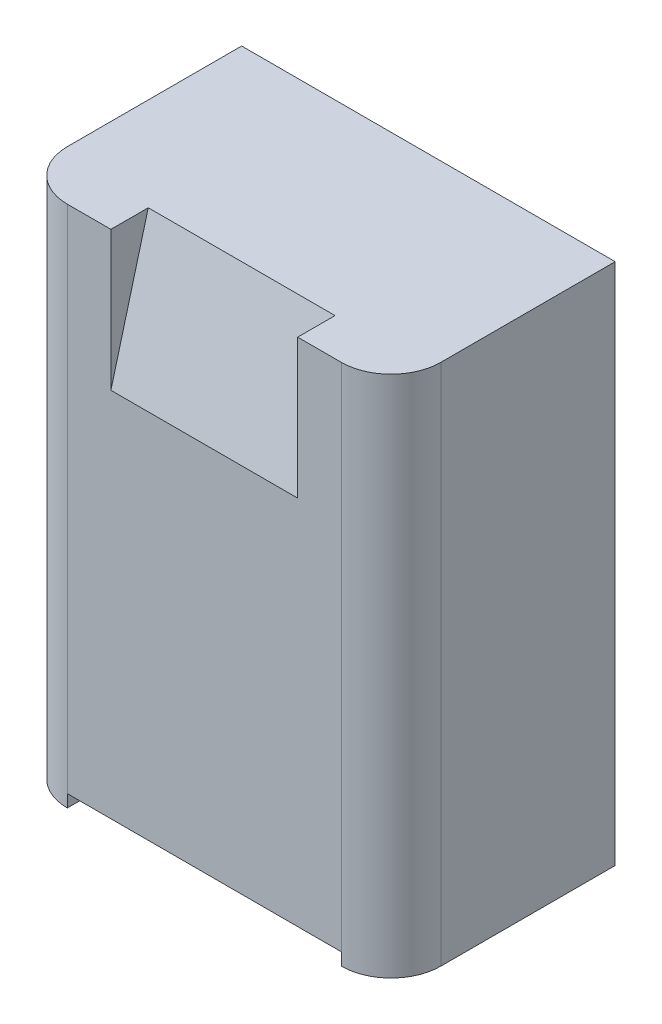
SolidWorks part; units mm, degrees
ref_plane "Front Plane" through (0, 0, 0) normal (0, 0, 1) x (1, 0, 0)
ref_plane "Top Plane" through (0, 0, 0) normal (0, 1, 0) x (1, 0, 0)
ref_plane "Right Plane" through (0, 0, 0) normal (1, 0, 0) x (0, 0, -1)
sketch "Sketch1" plane through (0, 0, 0) normal (0, 0, 1) x (1, 0, 0)
  line L0 (55, 0) -> (-55, 0) construction
  line L1 (-381, 0) -> (381, 0)
  line L2 (-381, 0) -> (-381, 1066.8)
  line L3 (-381, 1066.8) -> (381, 1066.8)
  line L4 (381, 0) -> (381, 1066.8)
  line L5 (0, 0) -> (0, 63.7993) construction
  line L6 (0, -55) -> (0, 55) construction
  dimension "D1" = 762
  dimension "D2" = 1066.8
extrude "Boss-Extrude1" add sketch "Sketch1" along normal mid plane 457.2
fillet "Fillet1" radius 101.6 2 edges at (381, 533.4, 228.6) (-381, 533.4, 228.6)
sketch "Sketch2" plane through (0, 0, 228.6) normal (0, 0, 1) x (1, 0, 0)
  line L0 (279.4, 0) -> (279.4, 1066.8) construction
  line L1 (-279.4, 0) -> (279.4, 0)
  line L2 (-279.4, 0) -> (-279.4, 25.4)
  line L3 (-279.4, 25.4) -> (279.4, 25.4)
  line L4 (279.4, 0) -> (279.4, 25.4)
  dimension "D1" = 25.4
extrude "Cut-Extrude1" cut sketch "Sketch2" against normal through all
sketch "Sketch3" plane through (0, 0, 0) normal (1, 0, 0) x (0, 0, -1)
  line L0 (-152.4, 1066.8) -> (-228.6, 782.4177)
  line L1 (-127, 1066.8) -> (228.6, 1066.8) construction
  line L2 (-228.6, 25.4) -> (-228.6, 1066.8) construction
  line L3 (-228.6, 782.4177) -> (-228.6, 1066.8)
  line L4 (-228.6, 1066.8) -> (-152.4, 1066.8)
  dimension "D1" = 15
  dimension "D2" = 76.2
extrude "Cut-Extrude2" cut sketch "Sketch3" against normal mid plane 381
